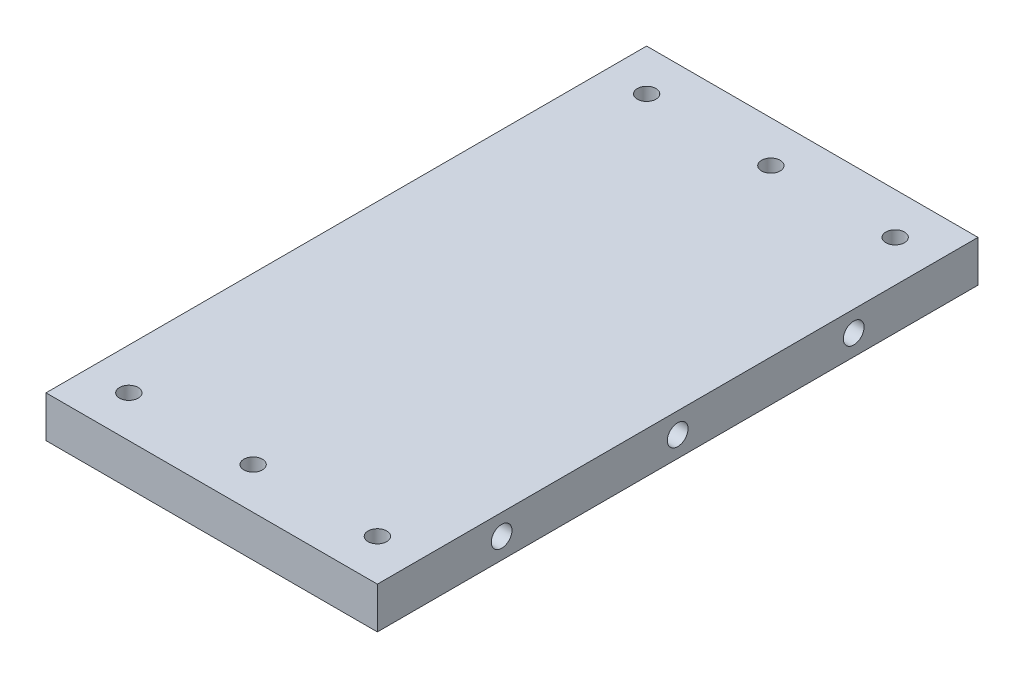
SolidWorks part; units mm, degrees
material "ABS"
ref_plane "Alzado" through (0, 0, 0) normal (0, 0, 1) x (1, 0, 0)
ref_plane "Planta" through (0, 0, 0) normal (0, 1, 0) x (1, 0, 0)
ref_plane "Vista lateral" through (0, 0, 0) normal (1, 0, 0) x (0, 0, -1)
sketch "Croquis1" plane through (0, 0, 0) normal (0, 1, 0) x (1, 0, 0)
  line L1 (-40, -72.5) -> (40, -72.5)
  line L2 (-40, -72.5) -> (-40, 72.5)
  line L3 (-40, 72.5) -> (40, 72.5)
  line L4 (40, -72.5) -> (40, 72.5)
  line L5 (-40, -72.5) -> (40, 72.5) construction
  line L6 (-40, 72.5) -> (40, -72.5) construction
  point P0 (0, 0)
  dimension "D1" = 80
  dimension "D2" = 145
extrude "Saliente-Extruir1" add sketch "Croquis1" along normal mid plane 10
sketch "Croquis2" plane through (40, 0, 0) normal (1, 0, 0) x (0, 0, -1)
  line L0 (42.5, 0) -> (-42.5, 0) construction
  line L1 (-72.5, 5) -> (-72.5, -5) construction
  circle A0 centre (0, 0) radius 2.5
  circle A1 centre (42.5, 0) radius 2.5
  circle A2 centre (-42.5, 0) radius 2.5
  point P4 (0, 0)
  dimension "D2" = 5
  dimension "D1" = 30
extrude "Cortar-Extruir1" cut sketch "Croquis2" against normal blind 10
mirror "Simetría1" about plane through (0, 0, 0) normal (1, 0, 0) of "Cortar-Extruir1"
sketch "Croquis3" plane through (0, -5, 0) normal (0, -1, 0) x (1, 0, 0)
  line L0 (0, 72.5) -> (0, 62.5) construction
  line L1 (-40, 72.5) -> (40, 72.5) construction
  line L2 (-30, 62.5) -> (30, 62.5) construction
  line L4 (5.5, 0) -> (-5.5, 0) construction
  circle A0 centre (-30, 62.5) radius 2.25
  circle A1 centre (0, 62.5) radius 2.25
  circle A2 centre (30, 62.5) radius 2.25
  circle A3 centre (30, -62.5) radius 2.25
  circle A4 centre (0, -62.5) radius 2.25
  circle A5 centre (-30, -62.5) radius 2.25
  point P8 (0, 62.5)
  dimension "D3" = 4.5
  dimension "D1" = 10
  dimension "D2" = 60
extrude "Cortar-Extruir2" cut sketch "Croquis3" against normal through all
